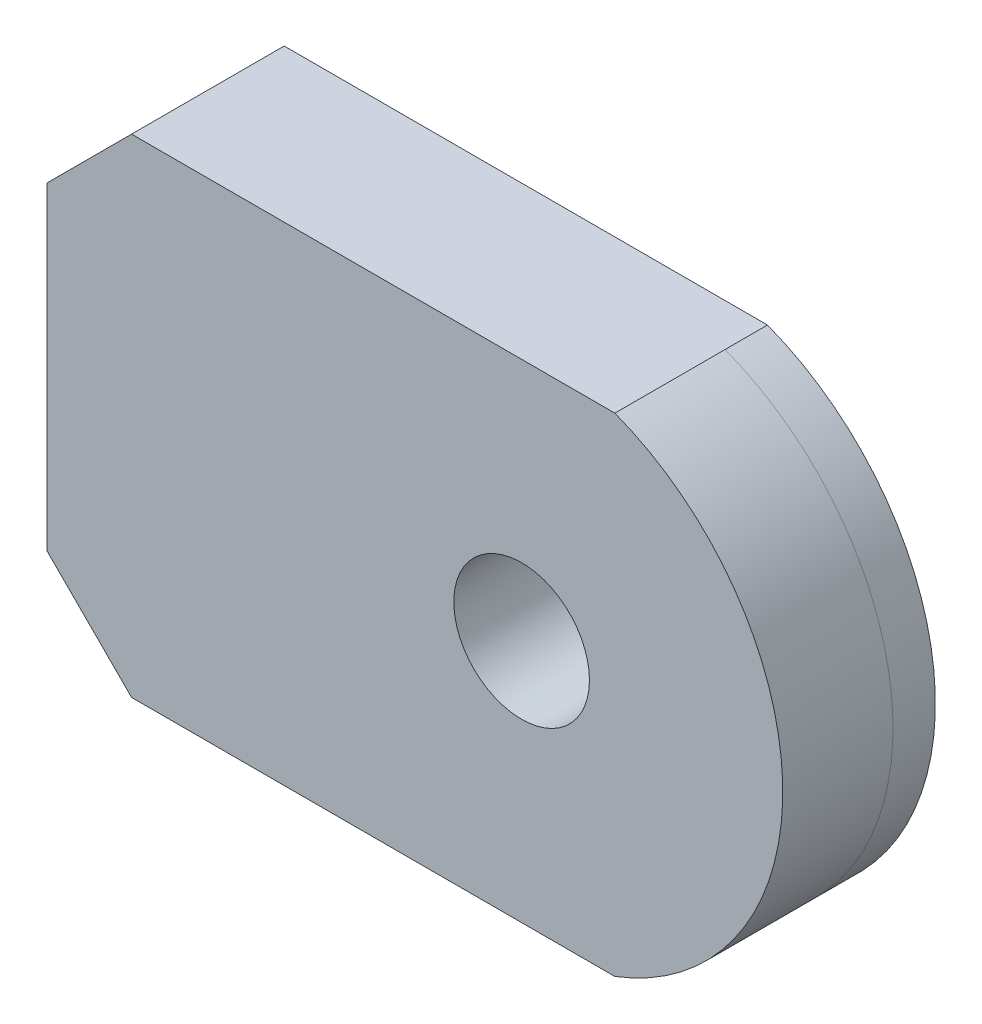
SolidWorks part; units mm, degrees
ref_plane "Plan de face" through (0, 0, 0) normal (0, 0, 1) x (1, 0, 0)
ref_plane "Plan de dessus" through (0, 0, 0) normal (0, 1, 0) x (1, 0, 0)
ref_plane "Plan de droite" through (0, 0, 0) normal (1, 0, 0) x (0, 0, -1)
sketch "Esquisse1" plane through (0, 0, 0) normal (0, 0, 1) x (1, 0, 0)
  line L0 (5, 28.77) -> (5, 0) construction
  line L1 (0, 0) -> (43, 0) construction
  line L2 (0, 0) -> (0, 28.77) construction
  line L3 (0, 28.77) -> (43, 28.77) construction
  line L4 (43, 0) -> (43, 28.77) construction
  line L5 (0, 23.77) -> (43, 23.77) construction
  line L6 (0, 5) -> (43, 5) construction
  line L7 (22.5, 0) -> (25, -8.6275) construction
  line L8 (31, -8.6275) -> (33.5, 0) construction
  line L9 (28, 48.77) -> (28, -20) construction
  line L10 (22.5, 51.4714) -> (22.5, -25.6838) construction
  line L11 (33.5, 48.77) -> (33.5, -20) construction
  line L12 (53.2237, 37.3975) -> (-15.7881, 37.3975) construction
  line L13 (53.2237, -8.6275) -> (-15.7881, -8.6275) construction
  line L14 (31, -25.6838) -> (31, 51.4714) construction
  line L15 (25, 51.4714) -> (25, -25.6838) construction
  line L16 (22.5, 28.77) -> (25, 37.3975) construction
  line L17 (31, 37.3975) -> (33.5, 28.77) construction
  line L18 (22.5, 28.77) -> (5, 28.77)
  line L19 (5, 28.77) -> (0, 23.77)
  line L20 (28, 28.77) -> (28, 0) construction
  line L21 (5, 0) -> (22.5, 0)
  line L22 (0, 23.77) -> (0, 5)
  line L23 (0, 5) -> (5, 0)
  line L24 (-4.4563, 30.6) -> (50.3143, 30.6) construction
  line L25 (50.3143, -1.83) -> (-4.4563, -1.83) construction
  line L26 (22.5, 0) -> (33.5, 0)
  line L27 (33.5, 28.77) -> (22.5, 28.77)
  line L28 (12.25, 0) -> (12.25, 28.77) construction
  line L29 (0, 14.385) -> (43.4006, 14.385) construction
  line L30 (28, 14.385) -> (48.1184, 34.5034) construction
  line L31 (28, 14.385) -> (48.0527, -5.6677) construction
  line L32 (28, 14.385) -> (15.5359, 1.9209) construction
  line L33 (14.9096, 27.4754) -> (28, 14.385) construction
  line L34 (39.704, -5.8869) -> (16.296, 34.6569) construction
  arc A0 (25, 37.3975) -> (31, 37.3975) centre (28, 37.3975) cw construction
  arc A1 (25, -8.6275) -> (31, -8.6275) centre (28, -8.6275) ccw construction
  circle A2 centre (28, 37.3975) radius 1.39 construction
  circle A3 centre (28, -8.6275) radius 1.39 construction
  arc A4 (33.5, 0) -> (33.5, 28.77) centre (28, 14.385) ccw
  circle A5 centre (28, 30.6) radius 1.5 construction
  circle A6 centre (28, -1.83) radius 1.5 construction
  circle A7 centre (12.25, 3.905) radius 1.98
  circle A8 centre (12.25, 24.865) radius 1.98
  circle A9 centre (28, 14.385) radius 6.3
  circle A10 centre (28, 14.385) radius 12.7 construction
  circle A11 centre (28, 14.385) radius 9.525 construction
  circle A12 centre (28, 4.86) radius 1.475
  circle A13 centre (28, 23.91) radius 1.475
  circle A14 centre (36.9803, 5.4047) radius 1.05
  circle A15 centre (36.9803, 23.3653) radius 1.05
  circle A16 centre (19.0197, 23.3653) radius 1.05
  circle A17 centre (19.0197, 5.4047) radius 1.05
  circle A18 centre (28, 14.385) radius 8 construction
  circle A19 centre (24, 21.3132) radius 0.85
  circle A20 centre (32, 7.4568) radius 0.85
  dimension "D13" = 20
  dimension "D19" = 3
  dimension "D20" = 2.78
  dimension "D21" = 2.78
  dimension "D22" = 3
  dimension "D25" = 3.96
  dimension "D26" = 25.4
  dimension "D27" = 12.6
  dimension "D28" = 19.05
  dimension "D29" = 2.95
  dimension "D32" = 2.1
  dimension "D33" = 16
  dimension "D35" = 1.7
  dimension "D1" = 5
  dimension "D2" = 5
  dimension "D3" = 5
  dimension "D4" = 28.77
  dimension "D5" = 43
  dimension "D6" = 28
  dimension "D7" = 5.5
  dimension "D8" = 5.5
  dimension "D9" = 23.0125
  dimension "D10" = 23.0125
  dimension "D11" = 3
  dimension "D12" = 3
  dimension "D14" = 20
  dimension "D15" = 20
  dimension "D16" = 20
  dimension "D17" = 16.215
  dimension "D18" = 16.215
  dimension "D23" = 15.75
  dimension "D24" = 20.96
  dimension "D30" = 45
  dimension "D31" = 45
  dimension "D34" = 30
extrude "Boss.-Extru.2" add sketch "Esquisse1" along normal blind 2.5
sketch "Esquisse2" plane through (0, 0, 2.5) normal (0, 0, 1) x (1, 0, 0)
  line L0 (5, 28.77) -> (33.5, 28.77)
  line L1 (33.5, 0) -> (5, 0)
  line L2 (5, 0) -> (0, 5)
  line L3 (0, 5) -> (0, 23.77)
  line L13 (5, 28.77) -> (0, 23.77)
  line L14 (0, 23.77) -> (0, 5)
  line L15 (0, 5) -> (5, 0)
  line L16 (5, 0) -> (33.5, 0)
  line L21 (33.5, 28.77) -> (5, 28.77)
  line L22 (5, 28.77) -> (0, 23.77)
  arc A0 (33.5, 28.77) -> (33.5, 0) centre (27.9998, 14.385) cw
  arc A6 (33.5, 0) -> (33.5, 28.77) centre (28, 14.385) ccw
  dimension "D1" = 0
extrude "Boss.-Extru.3" add sketch "Esquisse2" along normal blind 6.5
sketch "Esquisse3" plane through (0, 0, 9) normal (0, 0, 1) x (1, 0, 0)
  circle A0 centre (27.9998, 14.385) radius 4
  arc A1 (33.5, 0) -> (33.5, 28.77) centre (27.9998, 14.385) ccw construction
  dimension "D1" = 8
extrude "Enlèv. mat.-Extru.1" cut sketch "Esquisse3" against normal blind 10
